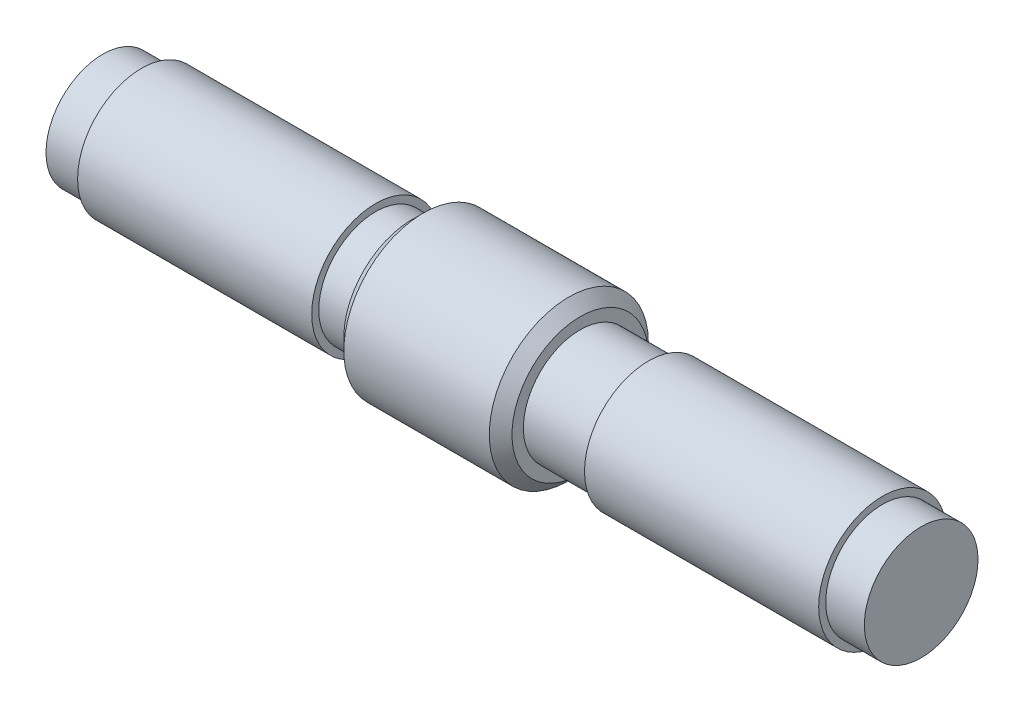
SolidWorks part; units mm, degrees
ref_plane "Frontal" through (0, 0, 0) normal (0, 0, 1) x (1, 0, 0)
ref_plane "Superior" through (0, 0, 0) normal (0, 1, 0) x (1, 0, 0)
ref_plane "Izquierda" through (0, 0, 0) normal (1, 0, 0) x (0, 0, -1)
sketch "Croquis1" plane through (0, 0, 0) normal (1, 0, 0) x (0, 0, -1)
  circle A0 centre (0, 0) radius 35
  dimension "D1" = 70
extrude "Saliente-Extruir1" add sketch "Croquis1" along normal mid plane 74
ref_plane "Plano1" through (7, 0, 0) normal (-1, 0, 0) x (0, 0, 1)
chamfer "Chaflán1" distance 5 angle 45 2 edges at (37, 0, -35) (-37, 0, -35)
sketch "Croquis2" plane through (-37, 0, 0) normal (-1, 0, 0) x (0, 0, 1)
  circle A0 centre (0, 0) radius 25
  dimension "D1" = 50
extrude "Saliente-Extruir2" add sketch "Croquis2" along normal blind 16
sketch "Croquis3" plane through (-53, 0, 0) normal (-1, 0, 0) x (0, 0, 1)
  circle A0 centre (0, 0) radius 28.1
  dimension "D1" = 56.2
extrude "Saliente-Extruir3" add sketch "Croquis3" along normal blind 120
chamfer "Chaflán2" [suppressed] distance 2.5 angle 45
sketch "Croquis4" plane through (37, 0, 0) normal (1, 0, 0) x (0, 0, -1)
  circle A0 centre (0, 0) radius 25
  dimension "D1" = 50
extrude "Saliente-Extruir4" add sketch "Croquis4" along normal blind 30
sketch "Croquis5" plane through (67, 0, 0) normal (1, 0, 0) x (0, 0, -1)
  circle A0 centre (0, 0) radius 28.1
  dimension "D1" = 56.2
extrude "Saliente-Extruir5" add sketch "Croquis5" along normal blind 120
chamfer "Chaflán3" [suppressed] distance 2.5 angle 45
sketch "Croquis6" plane through (-173, 0, 0) normal (-1, 0, 0) x (0, 0, 1)
  circle A0 centre (0, 0) radius 25
  circle A1 centre (0, 0) radius 28.1
extrude "Cortar-Extruir1" cut sketch "Croquis6" against normal blind 17
sketch "Croquis8" plane through (187, 0, 0) normal (1, 0, 0) x (0, 0, -1)
  circle A0 centre (0, 0) radius 25
  circle A1 centre (0, 0) radius 28.1
extrude "Cortar-Extruir2" cut sketch "Croquis8" against normal blind 17
